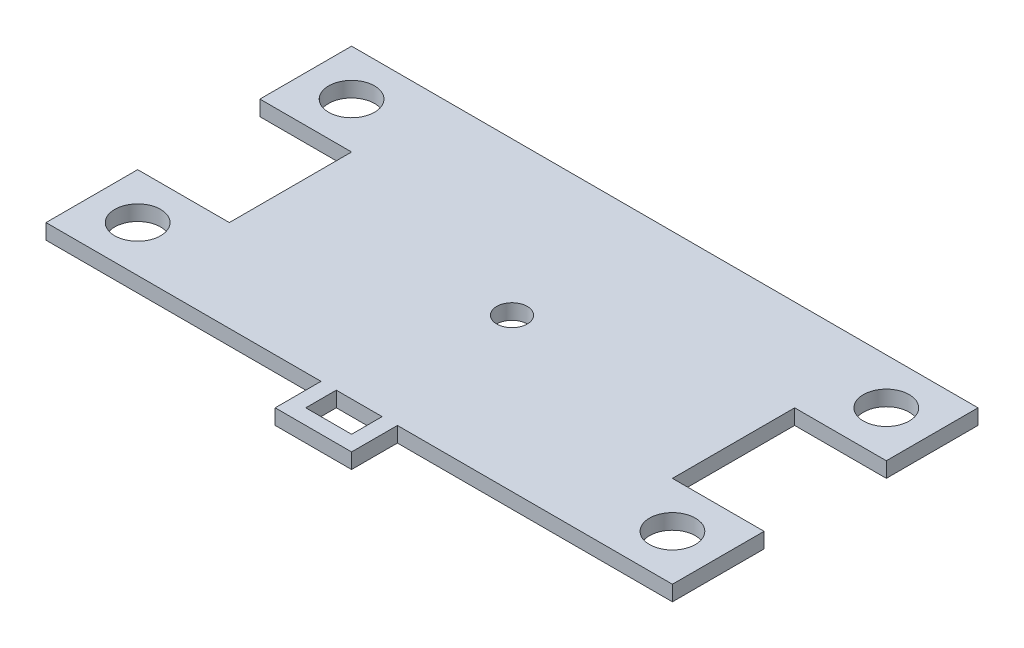
SolidWorks part; units mm, degrees
ref_plane "Alzado" through (0, 0, 0) normal (0, 0, 1) x (1, 0, 0)
ref_plane "Planta" through (0, 0, 0) normal (0, 1, 0) x (1, 0, 0)
ref_plane "Vista lateral" through (0, 0, 0) normal (1, 0, 0) x (0, 0, -1)
sketch "Croquis2" plane through (0, 0, 0) normal (0, 1, 0) x (1, 0, 0)
  line L0 (38, 17) -> (-3, 17)
  line L1 (0, 0) -> (35, 0) construction
  line L2 (0, 0) -> (0, 14) construction
  line L3 (0, 14) -> (35, 14) construction
  line L4 (35, 0) -> (35, 14) construction
  line L5 (-3, 17) -> (-3, 11)
  line L6 (-3, 11) -> (3, 11)
  line L7 (3, 11) -> (3, 3)
  line L8 (3, 3) -> (-3, 3)
  line L9 (-3, 3) -> (-3, -3)
  line L10 (-3, -3) -> (15, -3)
  line L11 (17.5, 17) -> (17.5, 14) construction
  line L12 (17.5, 0) -> (17.5, -3) construction
  line L13 (3, 7) -> (0, 7) construction
  line L14 (38, 3) -> (38, -3)
  line L15 (32, 3) -> (38, 3)
  line L16 (32, 11) -> (32, 3)
  line L17 (38, 11) -> (32, 11)
  line L18 (38, 17) -> (38, 11)
  line L19 (17.5, 0) -> (17.5, 14) construction
  line L20 (17.5, -3) -> (17.5, -5) construction
  line L22 (15, -3) -> (15, -6)
  line L23 (15, -6) -> (20, -6)
  line L24 (20, -3) -> (20, -6)
  line L26 (16, -3) -> (16, -5)
  line L27 (16, -5) -> (19, -5)
  line L28 (19, -3) -> (19, -5)
  line L29 (17.5, -5) -> (17.5, -6) construction
  line L30 (16, -3) -> (19, -3)
  line L31 (20, -3) -> (38, -3)
  circle A0 centre (0, 14) radius 1.5
  circle A1 centre (0, 0) radius 1.5
  circle A2 centre (35, 0) radius 1.5
  circle A3 centre (35, 14) radius 1.5
  circle A4 centre (17.5, 7) radius 1
  dimension "D1" = 3
  dimension "D8" = 2
  dimension "D2" = 14
  dimension "D3" = 35
  dimension "D4" = 3
  dimension "D5" = 3
  dimension "D6" = 8
  dimension "D7" = 20
  dimension "D9" = 3
  dimension "D10" = 5
  dimension "D11" = 1
  dimension "D12" = 2
extrude "Saliente-Extruir1" add sketch "Croquis2" along normal blind 1
